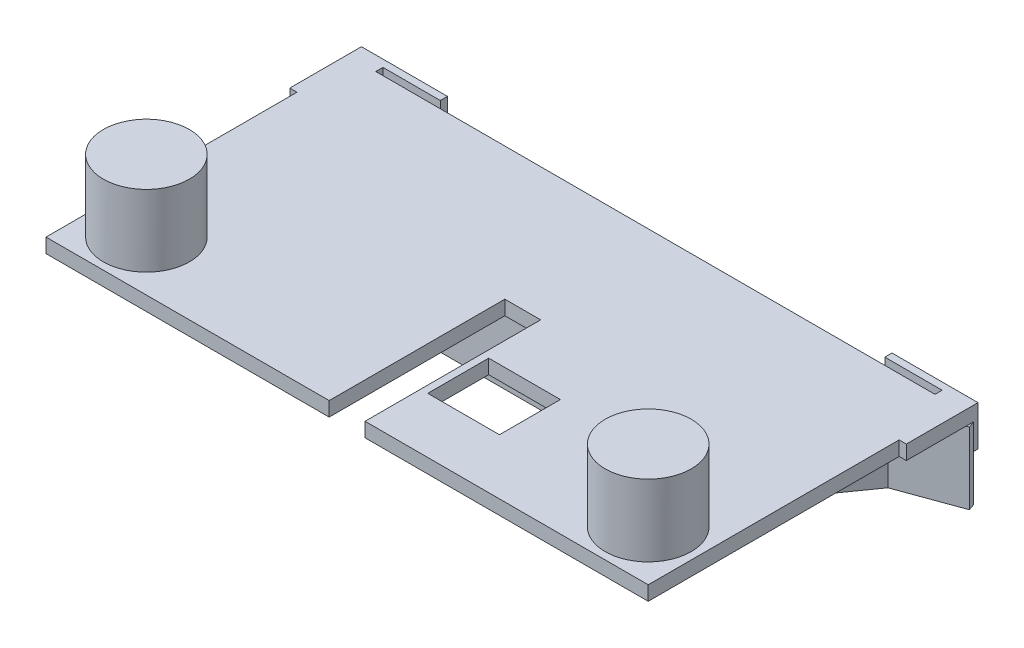
SolidWorks part; units mm, degrees
material "Oak"
ref_plane "Front Plane" through (0, 0, 0) normal (0, 0, 1) x (1, 0, 0)
ref_plane "Top Plane" through (0, 0, 0) normal (0, 1, 0) x (1, 0, 0)
ref_plane "Right Plane" through (0, 0, 0) normal (1, 0, 0) x (0, 0, -1)
sketch "Sketch1" plane through (0, 0, 0) normal (0, 1, 0) x (1, 0, 0)
  line L1 (-273.05, -139.7) -> (273.05, -139.7)
  line L2 (-273.05, -139.7) -> (-273.05, 139.7)
  line L3 (-273.05, 139.7) -> (273.05, 139.7)
  line L4 (273.05, -139.7) -> (273.05, 139.7)
  line L5 (-273.05, -139.7) -> (273.05, 139.7) construction
  line L6 (-273.05, 139.7) -> (273.05, -139.7) construction
  point P0 (0, 0)
  dimension "D1" = 279.4
  dimension "D2" = 546.1
extrude "Boss-Extrude1" add sketch "Sketch1" along normal mid plane 12.7
sketch "Sketch2" plane through (0, 6.35, 0) normal (0, 1, 0) x (1, 0, 0)
  line L0 (-273.05, -139.7) -> (273.05, -139.7) construction
  line L1 (-15.875, 15.875) -> (15.875, 15.875)
  line L2 (-15.875, 15.875) -> (-15.875, -139.7)
  line L3 (-15.875, -139.7) -> (15.875, -139.7)
  line L4 (15.875, 15.875) -> (15.875, -139.7)
  line L5 (-15.875, 15.875) -> (15.875, -139.7) construction
  line L6 (-15.875, -139.7) -> (15.875, 15.875) construction
  line L7 (-266.7, -139.7) -> (-266.7, 82.55)
  line L8 (22.225, -90.4875) -> (85.725, -90.4875)
  line L9 (22.225, -90.4875) -> (22.225, -36.5125)
  line L10 (22.225, -36.5125) -> (85.725, -36.5125)
  line L11 (-266.7, 82.55) -> (-273.05, 82.55)
  line L12 (22.225, -90.4875) -> (85.725, -36.5125) construction
  line L13 (22.225, -36.5125) -> (85.725, -90.4875) construction
  line L14 (-273.05, 82.55) -> (-273.05, -139.7)
  line L15 (-273.05, -139.7) -> (-266.7, -139.7)
  line L16 (85.725, -90.4875) -> (85.725, -36.5125)
  line L17 (273.05, 139.7) -> (-273.05, 139.7) construction
  line L18 (-247.65, 133.35) -> (247.65, 133.35)
  line L19 (-247.65, 133.35) -> (-247.65, 139.7)
  line L20 (-247.65, 139.7) -> (247.65, 139.7)
  line L21 (247.65, 133.35) -> (247.65, 139.7)
  line L22 (-247.65, 133.35) -> (247.65, 139.7) construction
  line L23 (-247.65, 139.7) -> (247.65, 133.35) construction
  line L24 (-273.05, 139.7) -> (-273.05, -139.7) construction
  line L25 (266.7, -139.7) -> (266.7, 82.55)
  line L26 (266.7, 82.55) -> (273.05, 82.55)
  line L27 (273.05, 82.55) -> (273.05, -139.7)
  line L28 (273.05, -139.7) -> (266.7, -139.7)
  point P0 (0, -61.9125)
  point P9 (53.975, -63.5)
  point P18 (0, 136.525)
  dimension "D1" = 31.75
  dimension "D2" = 155.575
  dimension "D3" = 53.975
  dimension "D4" = 6.35
  dimension "D5" = 63.5
  dimension "D6" = 49.2125
  dimension "D7" = 6.35
  dimension "D8" = 222.25
  dimension "D9" = 6.35
  dimension "D10" = 495.3
  dimension "D11" = 6.35
  dimension "D12" = 222.25
extrude "Cut-Extrude1" cut sketch "Sketch2" against normal through all
sketch "Sketch3" plane through (0, -6.35, 0) normal (0, -1, 0) x (1, 0, 0)
  line L0 (222.25, -116.9928) -> (155.687, -22.86)
  line L1 (-152.4, -29.21) -> (152.4, -29.21)
  line L2 (155.687, -22.86) -> (-155.687, -22.86)
  line L3 (-155.687, -22.86) -> (-222.25, -116.9928)
  line L4 (273.05, -139.7) -> (247.65, -139.7) construction
  line L5 (-218.2119, -122.2806) -> (-152.4, -29.21)
  line L8 (152.4, -29.21) -> (218.2119, -122.2806)
  line L10 (218.2119, -122.2806) -> (-218.2119, -122.2806) construction
  line L12 (155.687, -22.86) -> (-155.687, -22.86) construction
  line L13 (0, -42.3393) -> (0, -133.35) construction
  line L14 (-247.65, -133.35) -> (247.65, -133.35) construction
  line L15 (273.05, -82.55) -> (273.05, -139.7) construction
  line L16 (0, -133.35) -> (0, -122.2806) construction
  line L17 (222.25, -116.9928) -> (275.2218, -136.273)
  line L18 (275.2218, -136.273) -> (273.05, -142.24)
  line L19 (0, -142.24) -> (0, -42.3393) construction
  line L20 (273.05, -142.24) -> (218.2119, -122.2806)
  line L21 (-222.25, -116.9928) -> (-275.2218, -136.273)
  line L22 (-275.2218, -136.273) -> (-273.05, -142.24)
  line L23 (-273.05, -142.24) -> (-218.2119, -122.2806)
  line L24 (273.05, -142.24) -> (-273.05, -142.24) construction
  dimension "D2" = 6.35
  dimension "D3" = 6.35
  dimension "D4" = 546.1
  dimension "D5" = 444.5
  dimension "D6" = 304.8
  dimension "D7" = 104.14
  dimension "D8" = 6.35
  dimension "D9" = 6.35
  dimension "D10" = 160
  dimension "D11" = 6.35
  dimension "D12" = 2.54
extrude "Extrude2" add sketch "Sketch3" along normal blind 63.5
sketch "Sketch4" plane through (0, 6.35, 0) normal (0, 1, 0) x (1, 0, 0)
  line L0 (266.7, 82.55) -> (266.7, -139.7) construction
  line L2 (-247.65, 133.35) -> (247.65, 133.35) construction
  line L3 (-266.7, -139.7) -> (-266.7, 82.55) construction
  circle A0 centre (222.25, -95.25) radius 38.1
  circle A1 centre (-222.25, -95.25) radius 38.1
  dimension "D1" = 76.2
  dimension "D2" = 44.45
  dimension "D4" = 76.2
  dimension "D3" = 228.6
  dimension "D5" = 44.45
  dimension "D6" = 228.6
extrude "Boss-Extrude2" add sketch "Sketch4" along normal blind 63.5
sketch "Sketch5" plane through (0, 0, -139.7) normal (0, 0, -1) x (-1, 0, 0)
  line L1 (-273.05, 6.35) -> (-196.85, 6.35)
  line L2 (-273.05, 6.35) -> (-273.05, -29.21)
  line L3 (-273.05, -29.21) -> (-196.85, -29.21)
  line L4 (-196.85, 6.35) -> (-196.85, -29.21)
  line L5 (273.05, 6.35) -> (196.85, 6.35)
  line L6 (273.05, 6.35) -> (273.05, -29.21)
  line L7 (273.05, -29.21) -> (196.85, -29.21)
  line L8 (196.85, 6.35) -> (196.85, -29.21)
  dimension "D1" = 76.2
  dimension "D2" = 35.56
  dimension "D3" = 76.2
  dimension "D4" = 35.56
extrude "Boss-Extrude3" add sketch "Sketch5" along normal blind 6.35
